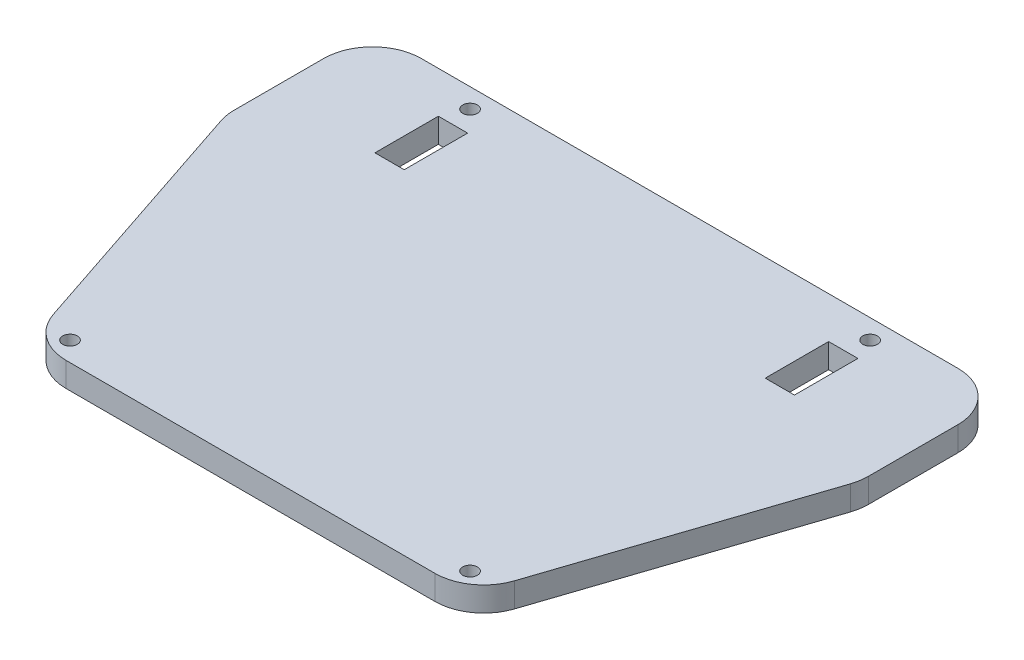
SolidWorks part; units mm, degrees
ref_plane "Front Plane" through (0, 0, 0) normal (0, 0, 1) x (1, 0, 0)
ref_plane "Top Plane" through (0, 0, 0) normal (0, 1, 0) x (1, 0, 0)
ref_plane "Right Plane" through (0, 0, 0) normal (1, 0, 0) x (0, 0, -1)
sketch "Sketch1" plane through (0, 0, 0) normal (0, 1, 0) x (1, 0, 0)
  line L0 (45, 90) -> (45, 0) construction
  line L1 (0, 0) -> (90, 0)
  line L2 (0, 0) -> (0, 90)
  line L3 (0, 90) -> (90, 90)
  line L4 (90, 0) -> (90, 90)
  line L5 (0, 90) -> (-20, 90)
  line L6 (-20, 90) -> (-20, 60)
  line L7 (-20, 60) -> (0, 0)
  line L8 (110, 60) -> (90, 0)
  line L9 (90, 90) -> (110, 90)
  line L10 (110, 90) -> (110, 60)
  line L11 (0, 45) -> (90, 45) construction
  line L13 (2, 68.5) -> (8, 68.5)
  line L14 (2, 68.5) -> (2, 81.5)
  line L15 (2, 81.5) -> (8, 81.5)
  line L16 (8, 68.5) -> (8, 81.5)
  line L17 (2, 68.5) -> (8, 81.5) construction
  line L18 (2, 81.5) -> (8, 68.5) construction
  line L22 (88, 81.5) -> (82, 81.5)
  line L23 (82, 68.5) -> (82, 81.5)
  line L24 (88, 68.5) -> (82, 68.5)
  line L25 (88, 68.5) -> (88, 81.5)
  circle A0 centre (4, 86) radius 1.5
  circle A1 centre (86, 86) radius 1.5
  circle A2 centre (86, 4) radius 1.5
  circle A3 centre (4, 4) radius 1.5
  point P21 (5, 75)
  point P22 (5, 75)
  dimension "D7" = 3
  dimension "D1" = 90
  dimension "D2" = 90
  dimension "D3" = 20
  dimension "D4" = 30
  dimension "D5" = 4
  dimension "D6" = 4
  dimension "D8" = 15
  dimension "D9" = 5
  dimension "D10" = 6
  dimension "D11" = 13
extrude "Boss-Extrude9" add sketch "Sketch1" along normal blind 5
fillet "Fillet2" radius 10 6 edges at (110, 2.5, -90) (110, 2.5, -60) (90, 2.5, 0) (0, 2.5, 0) (-20, 2.5, -60) (-20, 2.5, -90)
